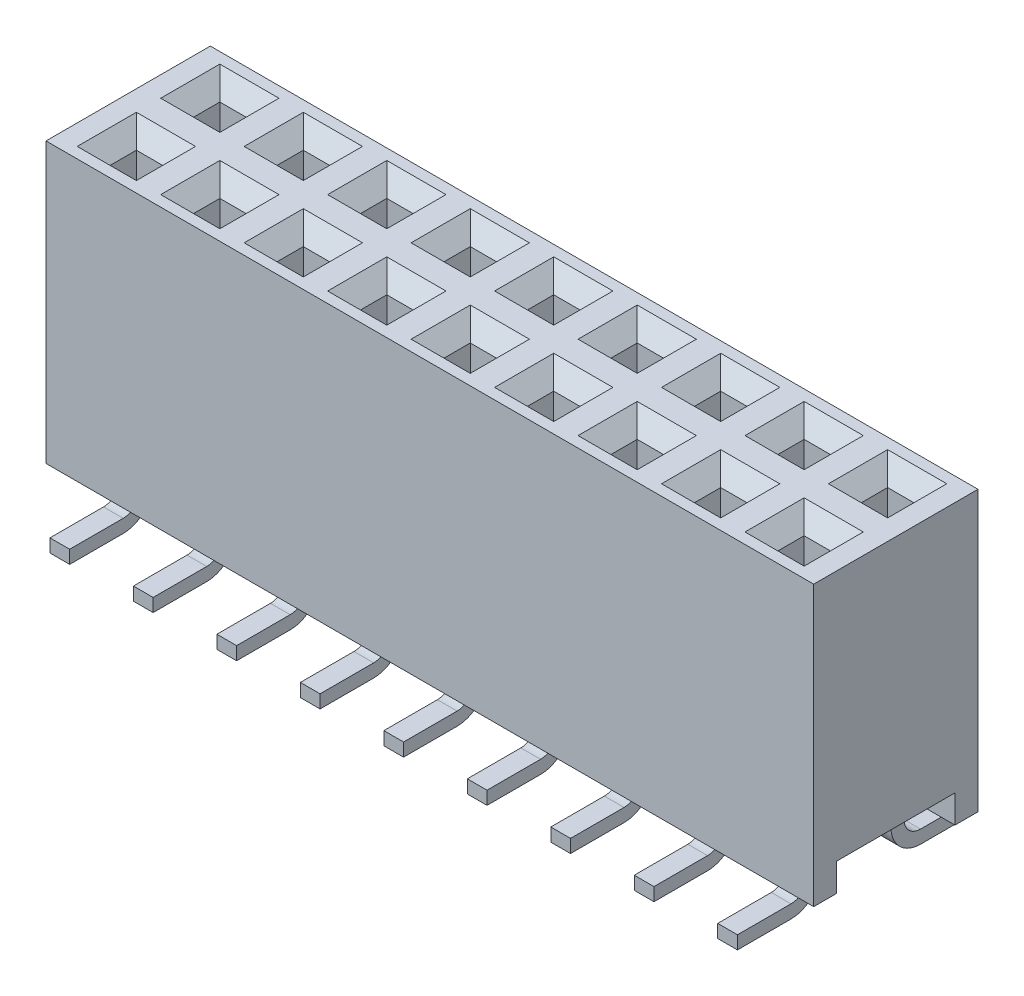
SolidWorks part; units mm, degrees
ref_plane "Спереди" through (0, 0, 0) normal (0, 0, 1) x (1, 0, 0)
ref_plane "Сверху" through (0, 0, 0) normal (0, 1, 0) x (1, 0, 0)
ref_plane "Справа" through (0, 0, 0) normal (1, 0, 0) x (0, 0, -1)
sketch "Эскиз1" plane through (0, 0, 0) normal (1, 0, 0) x (0, 0, -1)
  line L0 (-2.5, 1.2) -> (-2.5, 9.7)
  line L1 (-2.5, 9.7) -> (2.5, 9.7)
  line L2 (2.5, 9.7) -> (2.5, 1.2)
  line L3 (2.5, 1.2) -> (1.8, 1.2)
  line L4 (1.8, 1.2) -> (1.8, 2.05)
  line L5 (1.8, 2.05) -> (-1.8, 2.05)
  line L6 (-1.8, 2.05) -> (-1.8, 1.2)
  line L7 (-1.8, 1.2) -> (-2.5, 1.2)
  point P2 (0, 2.05)
  dimension "D1" = 5
  dimension "D2" = 8.5
  dimension "D3" = 0.85
  dimension "D4" = 0.7
  dimension "D5" = 1.2
extrude "Бобышка-Вытянуть1" add sketch "Эскиз1" against normal mid plane 23.36
sketch "Эскиз2" plane through (0, 9.7, 0) normal (0, 1, 0) x (1, 0, 0)
  line L1 (10.56, -1.67) -> (9.76, -1.67)
  line L2 (10.56, -1.67) -> (10.56, -0.87)
  line L3 (10.56, -0.87) -> (9.76, -0.87)
  line L4 (9.76, -1.67) -> (9.76, -0.87)
  line L5 (11.68, 2.5) -> (11.68, -2.5) construction
  point P4 (9.76, -1.27)
  point P8 (10.16, -1.67)
  dimension "D1" = 0.8
  dimension "D2" = 0.8
  dimension "D3" = 1.27
  dimension "D4" = 1.52
extrude "Вырез-Вытянуть1" cut sketch "Эскиз2" against normal through all
chamfer "Фаска1" distance 0.5 angle 45 4 edges at (10.56, 9.7, 1.27) (10.16, 9.7, 0.87) (9.76, 9.7, 1.27) (10.16, 9.7, 1.67)
pattern_linear "Линейный массив1" count 9 spacing 2.54 along (-1, 0, 0) count 2 spacing 2.54 along (0, 0, -1) of "Фаска1", "Вырез-Вытянуть1"
sketch "Эскиз3" plane through (0, 0, 0) normal (1, 0, 0) x (0, 0, -1)
  line L0 (-1.07, 0.9) -> (-1.07, 2.05)
  line L1 (-1.07, 2.05) -> (-1.47, 2.05)
  line L2 (-1.47, 2.05) -> (-1.47, 0.9)
  line L3 (-1.97, 0.4) -> (-3.6, 0.4)
  line L4 (-3.6, 0.4) -> (-3.6, 0)
  line L5 (-3.6, 0) -> (-1.97, 0)
  line L6 (-1.8, 2.05) -> (1.8, 2.05) construction
  arc A0 (-1.47, 0.9) -> (-1.97, 0.4) centre (-1.97, 0.9) cw
  arc A1 (-1.07, 0.9) -> (-1.97, 0) centre (-1.97, 0.9) cw
  point P8 (-1.27, 2.05)
  point P14 (0, 0)
  dimension "D4" = 0.5
  dimension "D1" = 0.4
  dimension "D2" = 1.27
  dimension "D3" = 3.6
extrude "Бобышка-Вытянуть2" add sketch "Эскиз3" along normal mid plane 0.6 separate body
pattern_linear "Линейный массив2" count 5 spacing 2.54 along (1, 0, 0) of bodies 104
pattern_linear "Линейный массив3" count 5 spacing 2.54 along (-1, 0, 0) of bodies 104
mirror "Зеркальное отражение1" about plane through (0, 0, 0) normal (0, 0, 1) of bodies 112 111 110 109 104 105 106 107 108
